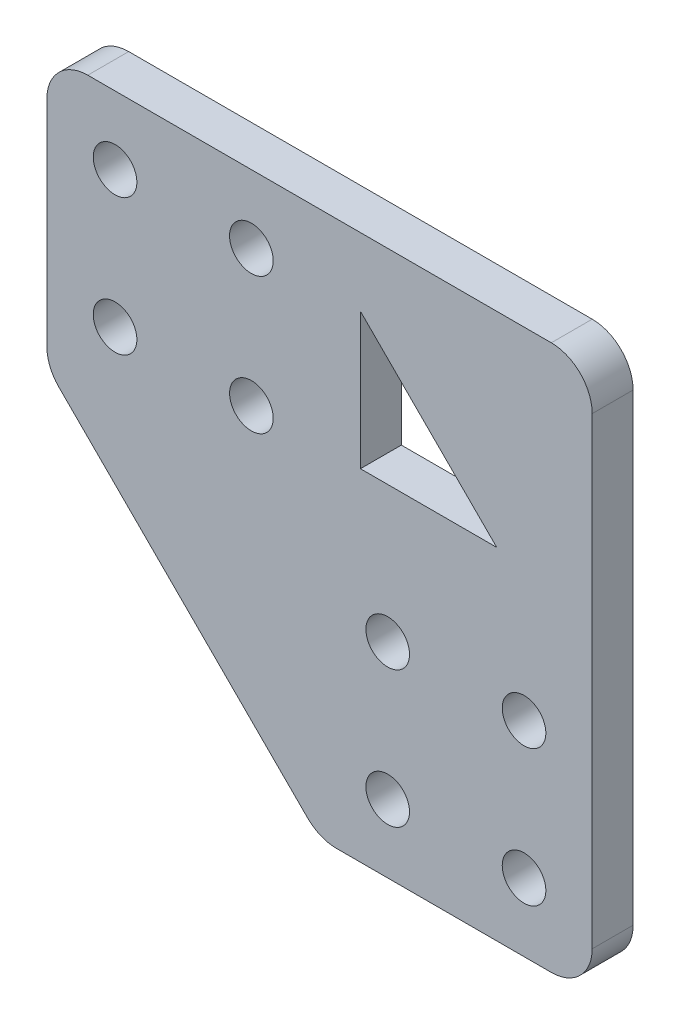
SolidWorks part; units mm, degrees
ref_plane "前视基准面" through (0, 0, 0) normal (0, 0, 1) x (1, 0, 0)
ref_plane "上视基准面" through (0, 0, 0) normal (0, 1, 0) x (1, 0, 0)
ref_plane "右视基准面" through (0, 0, 0) normal (1, 0, 0) x (0, 0, -1)
other "Configuration Table"
sketch "草图1" plane through (0, 0, 0) normal (0, 0, 1) x (1, 0, 0)
  line L0 (0, 0) -> (40, 0)
  line L3 (40, -40) -> (20, -40)
  line L4 (20, -40) -> (0, -20)
  line L5 (0, -20) -> (0, 0)
  line L6 (30, 0) -> (30, -40) construction
  line L7 (0, -10) -> (30, -10) construction
  line L8 (10, -10) -> (10, 0) construction
  line L9 (30, -30) -> (10, -30) construction
  line L10 (23, -5) -> (23, -15)
  line L11 (23, -15) -> (33, -15)
  line L12 (33, -15) -> (23, -5)
  line L16 (40, 0) -> (40, -40)
  circle A0 centre (5, -5) radius 1.6
  circle A1 centre (15, -5) radius 1.6
  circle A2 centre (15, -15) radius 1.6
  circle A3 centre (5, -15) radius 1.6
  circle A8 centre (25, -35) radius 1.6
  circle A9 centre (35, -35) radius 1.6
  circle A10 centre (35, -25) radius 1.6
  circle A11 centre (25, -25) radius 1.6
  point P3 (22.7217, -40)
  point P23 (30, 0)
  dimension "D8" = 3.2
  dimension "D11" = 3.2
  dimension "D2" = 20
  dimension "D3" = 20
  dimension "D4" = 40
  dimension "D5" = 40
  dimension "D6" = 10
  dimension "D7" = 10
  dimension "D9" = 5
  dimension "D10" = 5
  dimension "D12" = 5
  dimension "D13" = 5
  dimension "D14" = 10
  dimension "D15" = 10
  dimension "D19" = 7
extrude "凸台-拉伸1" add sketch "草图1" along normal blind 3
fillet "圆角1" radius 3 5 edges at (20, -40, 1.5) (40, -40, 1.5) (40, 0, 1.5) (0, -20, 1.5) (0, 0, 1.5)
